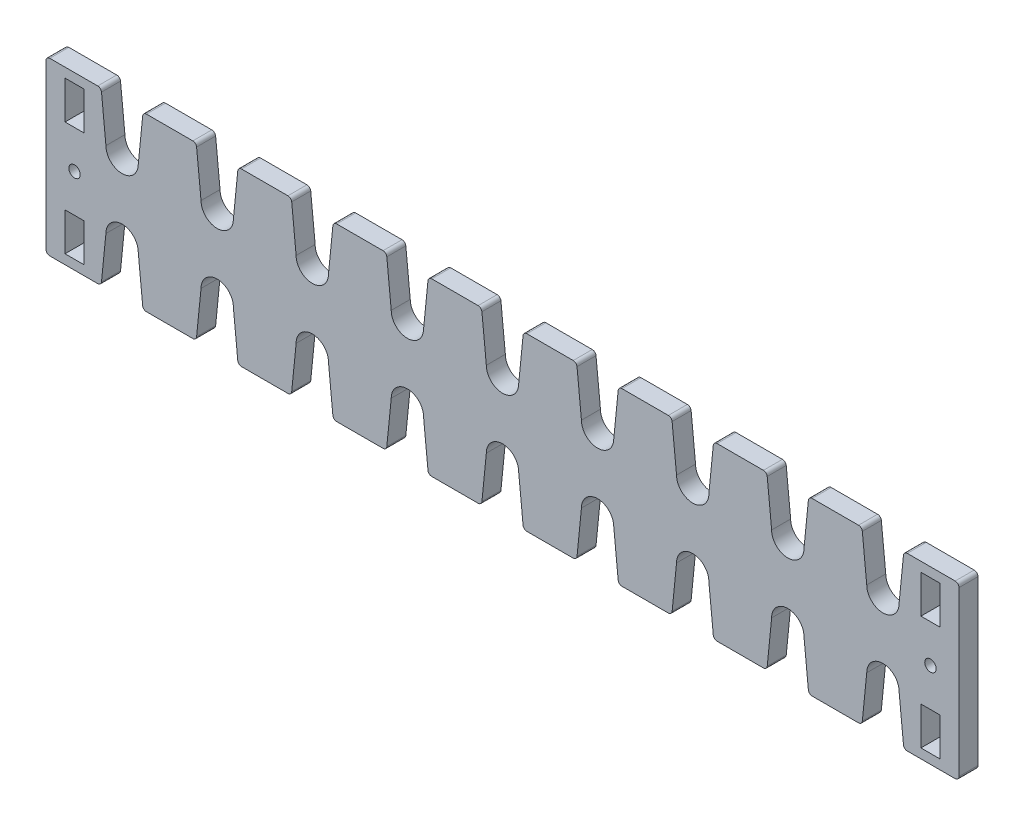
SolidWorks part; units mm, degrees
ref_plane "Front Plane" through (0, 0, 0) normal (0, 0, 1) x (1, 0, 0)
ref_plane "Top Plane" through (0, 0, 0) normal (0, 1, 0) x (1, 0, 0)
ref_plane "Right Plane" through (0, 0, 0) normal (1, 0, 0) x (0, 0, -1)
sketch "Sketch1" plane through (0, 0, 0) normal (0, 0, 1) x (1, 0, 0)
  line L0 (-90.218, 10) -> (299.3045, 10) construction
  line L1 (-85.8133, 22.5) -> (154.1867, 22.5)
  line L2 (-85.8133, 22.5) -> (-85.8133, -22.5)
  line L3 (-85.8133, -22.5) -> (154.1867, -22.5)
  line L4 (154.1867, 22.5) -> (154.1867, -22.5)
  line L5 (-80.8133, -10) -> (-75.8133, -10)
  line L6 (-91.3268, 0) -> (299.3045, 0) construction
  line L7 (-80.8133, 20) -> (-75.8133, 20)
  line L8 (-80.8133, 20) -> (-80.8133, 10)
  line L9 (-80.8133, 10) -> (-75.8133, 10)
  line L10 (-75.8133, 20) -> (-75.8133, 10)
  line L11 (-75.8133, -20) -> (-75.8133, -10)
  line L12 (-80.8133, -20) -> (-75.8133, -20)
  line L13 (-80.8133, -20) -> (-80.8133, -10)
  line L14 (34.1867, 30.0157) -> (34.1867, -45.8134) construction
  line L15 (-78.3133, 24.0051) -> (-78.3133, -32.23) construction
  line L16 (149.1867, -20) -> (149.1867, -10)
  line L17 (149.1867, -20) -> (144.1867, -20)
  line L18 (144.1867, -20) -> (144.1867, -10)
  line L19 (149.1867, -10) -> (144.1867, -10)
  line L20 (149.1867, 10) -> (144.1867, 10)
  line L21 (144.1867, 20) -> (144.1867, 10)
  line L22 (149.1867, 20) -> (144.1867, 20)
  line L23 (149.1867, 20) -> (149.1867, 10)
  circle A31 centre (-78.3133, 0) radius 1.5
  circle A32 centre (146.6867, 0) radius 1.5
  point P6 (34.1867, -22.5)
  point P13 (-85.8133, 0)
  point P82 (-78.3133, 20)
  dimension "D1" = 45
  dimension "D2" = 240
  dimension "D3" = 12.5
  dimension "D4" = 10
  dimension "D7" = 5
  dimension "D8" = 5
extrude "Boss-Extrude1" add sketch "Sketch1" along normal blind 5
sketch "Sketch2" plane through (0, 0, 5) normal (0, 0, 1) x (1, 0, 0)
  line L0 (-65.8133, 26.1544) -> (-65.8133, -32.4929) construction
  line L1 (-85.8133, 22.5) -> (-85.8133, -22.5) construction
  line L2 (154.1867, 22.5) -> (-85.8133, 22.5) construction
  line L3 (-71.3133, 22.5) -> (-60.3133, 22.5)
  line L4 (-71.3133, 22.5) -> (-70.0633, 10)
  line L6 (-60.3133, 22.5) -> (-61.5633, 10)
  line L7 (-86.9763, 0) -> (351.4175, 0) construction
  line L8 (-46.3133, 22.5) -> (-35.3133, 22.5)
  line L9 (-46.3133, 22.5) -> (-45.0633, 10)
  line L10 (-35.3133, 22.5) -> (-36.5633, 10)
  line L11 (-21.3133, 22.5) -> (-10.3133, 22.5)
  line L12 (-21.3133, 22.5) -> (-20.0633, 10)
  line L13 (-10.3133, 22.5) -> (-11.5633, 10)
  line L14 (3.6867, 22.5) -> (14.6867, 22.5)
  line L15 (3.6867, 22.5) -> (4.9367, 10)
  line L16 (14.6867, 22.5) -> (13.4367, 10)
  line L17 (28.6867, 22.5) -> (39.6867, 22.5)
  line L18 (28.6867, 22.5) -> (29.9367, 10)
  line L19 (39.6867, 22.5) -> (38.4367, 10)
  line L20 (53.6867, 22.5) -> (64.6867, 22.5)
  line L21 (53.6867, 22.5) -> (54.9367, 10)
  line L22 (64.6867, 22.5) -> (63.4367, 10)
  line L23 (78.6867, 22.5) -> (89.6867, 22.5)
  line L24 (78.6867, 22.5) -> (79.9367, 10)
  line L25 (89.6867, 22.5) -> (88.4367, 10)
  line L26 (103.6867, 22.5) -> (114.6867, 22.5)
  line L27 (103.6867, 22.5) -> (104.9367, 10)
  line L28 (114.6867, 22.5) -> (113.4367, 10)
  line L29 (128.6867, 22.5) -> (139.6867, 22.5)
  line L30 (128.6867, 22.5) -> (129.9367, 10)
  line L31 (139.6867, 22.5) -> (138.4367, 10)
  line L68 (139.6867, -22.5) -> (138.4367, -10)
  line L69 (128.6867, -22.5) -> (129.9367, -10)
  line L70 (128.6867, -22.5) -> (139.6867, -22.5)
  line L71 (114.6867, -22.5) -> (113.4367, -10)
  line L72 (103.6867, -22.5) -> (104.9367, -10)
  line L73 (103.6867, -22.5) -> (114.6867, -22.5)
  line L74 (89.6867, -22.5) -> (88.4367, -10)
  line L75 (78.6867, -22.5) -> (79.9367, -10)
  line L76 (78.6867, -22.5) -> (89.6867, -22.5)
  line L77 (64.6867, -22.5) -> (63.4367, -10)
  line L78 (53.6867, -22.5) -> (54.9367, -10)
  line L79 (53.6867, -22.5) -> (64.6867, -22.5)
  line L80 (39.6867, -22.5) -> (38.4367, -10)
  line L81 (28.6867, -22.5) -> (29.9367, -10)
  line L82 (28.6867, -22.5) -> (39.6867, -22.5)
  line L83 (14.6867, -22.5) -> (13.4367, -10)
  line L84 (3.6867, -22.5) -> (4.9367, -10)
  line L85 (3.6867, -22.5) -> (14.6867, -22.5)
  line L86 (-10.3133, -22.5) -> (-11.5633, -10)
  line L87 (-21.3133, -22.5) -> (-20.0633, -10)
  line L88 (-21.3133, -22.5) -> (-10.3133, -22.5)
  line L89 (-35.3133, -22.5) -> (-36.5633, -10)
  line L90 (-46.3133, -22.5) -> (-45.0633, -10)
  line L91 (-46.3133, -22.5) -> (-35.3133, -22.5)
  line L92 (-60.3133, -22.5) -> (-61.5633, -10)
  line L93 (-71.3133, -22.5) -> (-70.0633, -10)
  line L94 (-71.3133, -22.5) -> (-60.3133, -22.5)
  line L95 (-72.1736, 10) -> (-58.9603, 10) construction
  arc A0 (-70.0633, 10) -> (-61.5633, 10) centre (-65.8133, 10) ccw
  arc A1 (-45.0633, 10) -> (-36.5633, 10) centre (-40.8133, 10) ccw
  arc A2 (-20.0633, 10) -> (-11.5633, 10) centre (-15.8133, 10) ccw
  arc A3 (4.9367, 10) -> (13.4367, 10) centre (9.1867, 10) ccw
  arc A4 (29.9367, 10) -> (38.4367, 10) centre (34.1867, 10) ccw
  arc A5 (54.9367, 10) -> (63.4367, 10) centre (59.1867, 10) ccw
  arc A6 (79.9367, 10) -> (88.4367, 10) centre (84.1867, 10) ccw
  arc A7 (104.9367, 10) -> (113.4367, 10) centre (109.1867, 10) ccw
  arc A8 (129.9367, 10) -> (138.4367, 10) centre (134.1867, 10) ccw
  arc A21 (129.9367, -10) -> (138.4367, -10) centre (134.1867, -10) cw
  arc A22 (104.9367, -10) -> (113.4367, -10) centre (109.1867, -10) cw
  arc A23 (79.9367, -10) -> (88.4367, -10) centre (84.1867, -10) cw
  arc A24 (54.9367, -10) -> (63.4367, -10) centre (59.1867, -10) cw
  arc A25 (29.9367, -10) -> (38.4367, -10) centre (34.1867, -10) cw
  arc A26 (4.9367, -10) -> (13.4367, -10) centre (9.1867, -10) cw
  arc A27 (-20.0633, -10) -> (-11.5633, -10) centre (-15.8133, -10) cw
  arc A28 (-45.0633, -10) -> (-36.5633, -10) centre (-40.8133, -10) cw
  arc A29 (-70.0633, -10) -> (-61.5633, -10) centre (-65.8133, -10) cw
  point P10 (-65.8133, 22.5)
  dimension "D1" = 20
  dimension "D2" = 11
  dimension "D3" = 9
  dimension "D4" = 8.5
extrude "Cut-Extrude1" cut sketch "Sketch2" against normal blind 5
fillet "Fillet1" radius 1 40 edges at (154.1867, 22.5, 2.5) (154.1867, -22.5, 2.5) (-85.8133, 22.5, 2.5) (-85.8133, -22.5, 2.5) (-60.3133, -22.5, 2.5) (-71.3133, -22.5, 2.5) (-35.3133, -22.5, 2.5) (-46.3133, -22.5, 2.5) (-10.3133, -22.5, 2.5) (-21.3133, -22.5, 2.5) (14.6867, -22.5, 2.5) (3.6867, -22.5, 2.5) (39.6867, -22.5, 2.5) (28.6867, -22.5, 2.5) (64.6867, -22.5, 2.5) (53.6867, -22.5, 2.5) (89.6867, -22.5, 2.5) (78.6867, -22.5, 2.5) (103.6867, -22.5, 2.5) (114.6867, -22.5, 2.5) (128.6867, -22.5, 2.5) (139.6867, -22.5, 2.5) (139.6867, 22.5, 2.5) (128.6867, 22.5, 2.5) (114.6867, 22.5, 2.5) (103.6867, 22.5, 2.5) (89.6867, 22.5, 2.5) (78.6867, 22.5, 2.5) (64.6867, 22.5, 2.5) (39.6867, 22.5, 2.5) (53.6867, 22.5, 2.5) (28.6867, 22.5, 2.5) (14.6867, 22.5, 2.5) (3.6867, 22.5, 2.5) (-10.3133, 22.5, 2.5) (-21.3133, 22.5, 2.5) (-35.3133, 22.5, 2.5) (-46.3133, 22.5, 2.5) (-71.3133, 22.5, 2.5) (-60.3133, 22.5, 2.5)
